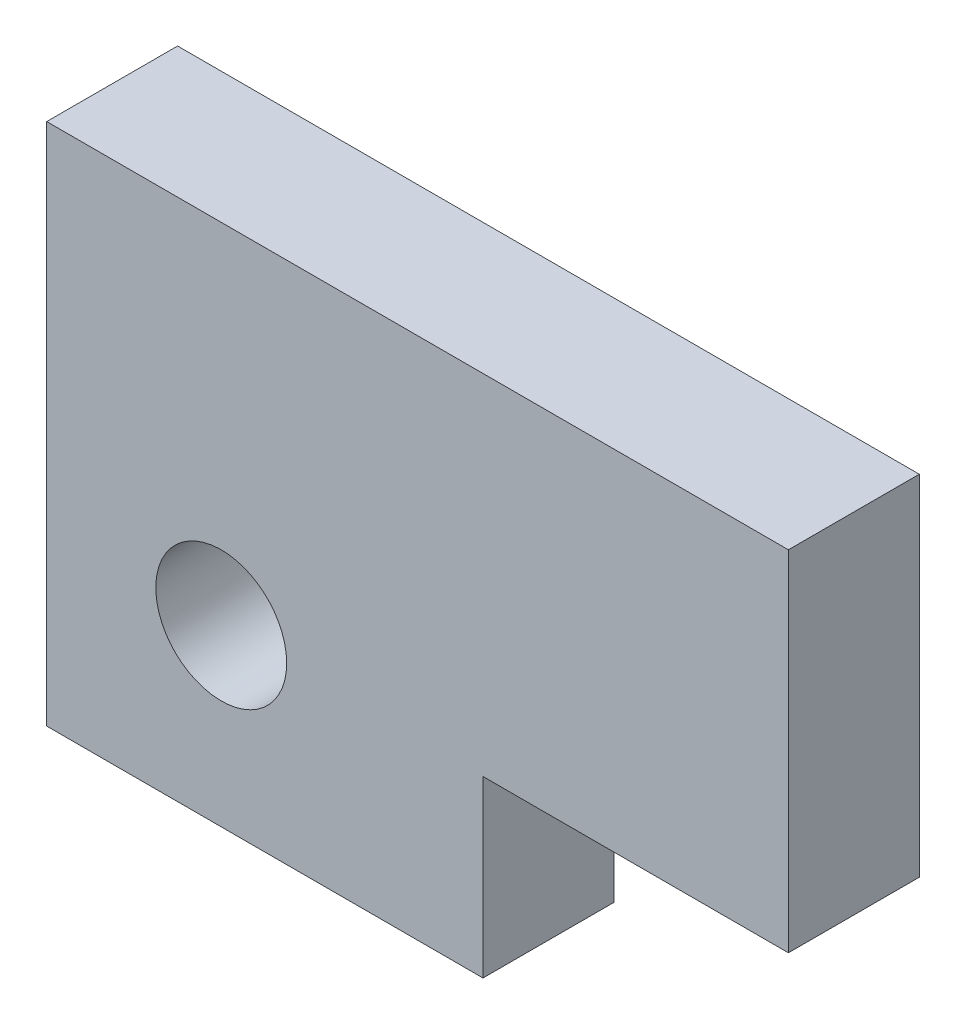
SolidWorks part; units mm, degrees
ref_plane "Спереди" through (0, 0, 0) normal (0, 0, 1) x (1, 0, 0)
ref_plane "Сверху" through (0, 0, 0) normal (0, 1, 0) x (1, 0, 0)
ref_plane "Справа" through (0, 0, 0) normal (1, 0, 0) x (0, 0, -1)
other "Configuration Table"
sketch "Эскиз1" plane through (0, 0, 0) normal (0, 0, 1) x (1, 0, 0)
  line L0 (8.5, 12) -> (8.5, 0) construction
  line L1 (0, 0) -> (10, 0)
  line L2 (0, 0) -> (0, 12)
  line L3 (0, 12) -> (17, 12)
  line L4 (17, 4) -> (17, 12)
  line L5 (0, 6) -> (18, 6) construction
  line L6 (17, 4) -> (10, 4)
  line L7 (10, 4) -> (10, 0)
  dimension "D1" = 17
  dimension "D2" = 12
  dimension "D3" = 7
  dimension "D4" = 4
extrude "Бобышка-Вытянуть1" add sketch "Эскиз1" along normal blind 3
sketch "Эскиз2" plane through (0, 0, 3) normal (0, 0, 1) x (1, 0, 0)
  line L0 (0, 0) -> (10, 0) construction
  line L7 (0, 12) -> (0, 0) construction
  circle A0 centre (4, 4) radius 1.5
  dimension "D1" = 3
  dimension "D2" = 4
  dimension "D3" = 4
extrude "Вырез-Вытянуть1" cut sketch "Эскиз2" against normal through all
